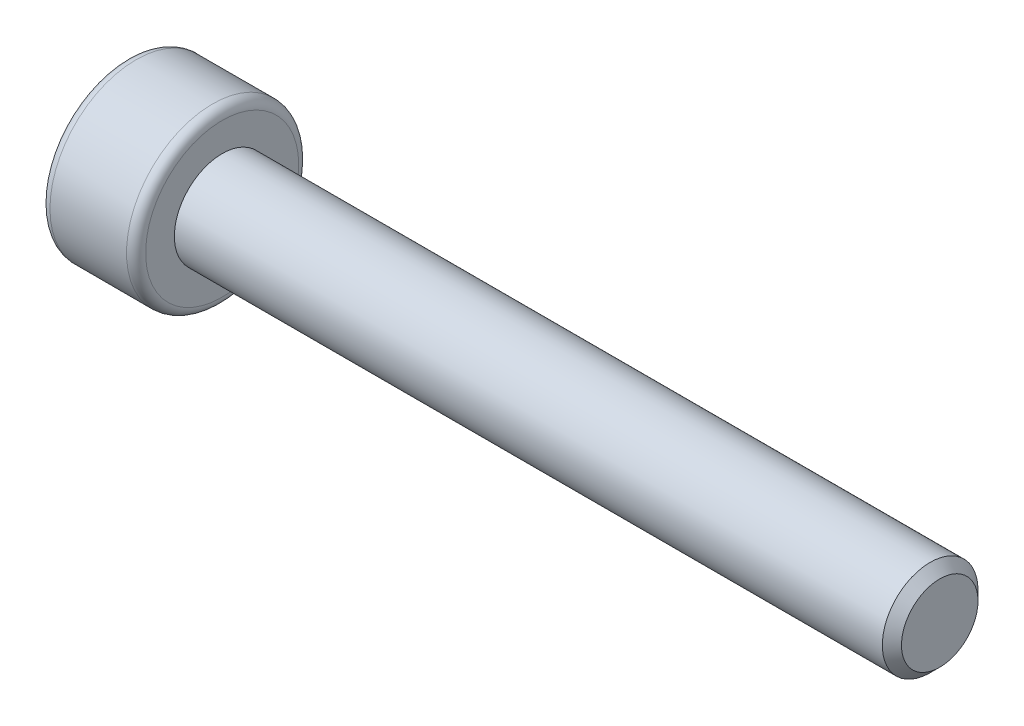
SolidWorks part; units mm, degrees
ref_plane "前视基准面" through (0, 0, 0) normal (0, 0, 1) x (1, 0, 0)
ref_plane "上视基准面" through (0, 0, 0) normal (0, 1, 0) x (1, 0, 0)
ref_plane "右视基准面" through (0, 0, 0) normal (1, 0, 0) x (0, 0, -1)
sketch "草图1" plane through (0, 0, 0) normal (0, 0, 1) x (1, 0, 0)
  line L0 (-8.5, 0) -> (-8.5, 1.8)
  line L1 (-8.5, 1.8) -> (-6.5, 1.8)
  line L2 (-6.5, 1.8) -> (-6.5, 1)
  line L3 (-6.5, 1) -> (8.5, 1)
  line L4 (8.5, 1) -> (8.5, 0)
  line L5 (8.5, 0) -> (-8.5, 0) construction
  line L6 (-8.5, 0) -> (8.5, 0)
  dimension "D1" = 3.6
  dimension "D2" = 2
  dimension "D3" = 2
  dimension "D4" = 15
revolve "旋转1" add sketch "草图1" angle 360 about L5
sketch "草图2" plane through (-8.5, 0, 0) normal (-1, 0, 0) x (0, 0, 1)
  line L1 (0.866, 0) -> (0.433, 0.75)
  line L2 (0.433, 0.75) -> (-0.433, 0.75)
  line L3 (-0.433, 0.75) -> (-0.866, 0)
  line L4 (-0.866, 0) -> (-0.433, -0.75)
  line L5 (-0.433, -0.75) -> (0.433, -0.75)
  line L6 (0.433, -0.75) -> (0.866, 0)
  circle A0 centre (0, 0) radius 0.75 construction
  dimension "D1" = 1.5
extrude "切除-拉伸1" cut sketch "草图2" against normal blind 1.5
fillet "圆角1" radius 0.2 2 edges at (-6.5, 0, -1.8) (-8.5, 0, -1.8)
chamfer "倒角1" distance 0.2 angle 45 1 edges at (8.5, 0, -1)
